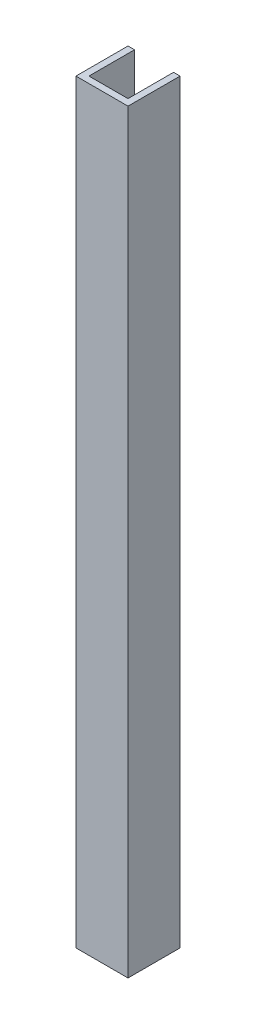
SolidWorks part; units mm, degrees
material "1060 Alloy"
ref_plane "Front Plane" through (0, 0, 0) normal (0, 0, 1) x (1, 0, 0)
ref_plane "Top Plane" through (0, 0, 0) normal (0, 1, 0) x (1, 0, 0)
ref_plane "Right Plane" through (0, 0, 0) normal (1, 0, 0) x (0, 0, -1)
sketch "Sketch1" plane through (0, 0, 0) normal (0, 1, 0) x (1, 0, 0)
  line L0 (0, 0) -> (25.4, 0)
  line L1 (25.4, 0) -> (25.4, 25.4)
  line L7 (0, 25.4) -> (0, 0)
  dimension "D1" = 25.4
  dimension "D2" = 25.4
  dimension "D3" = 25.4
extrude "Extrude-Thin1" add sketch "Sketch1" along normal blind 368.3 thin thin type one direction reverse wall 3.175
